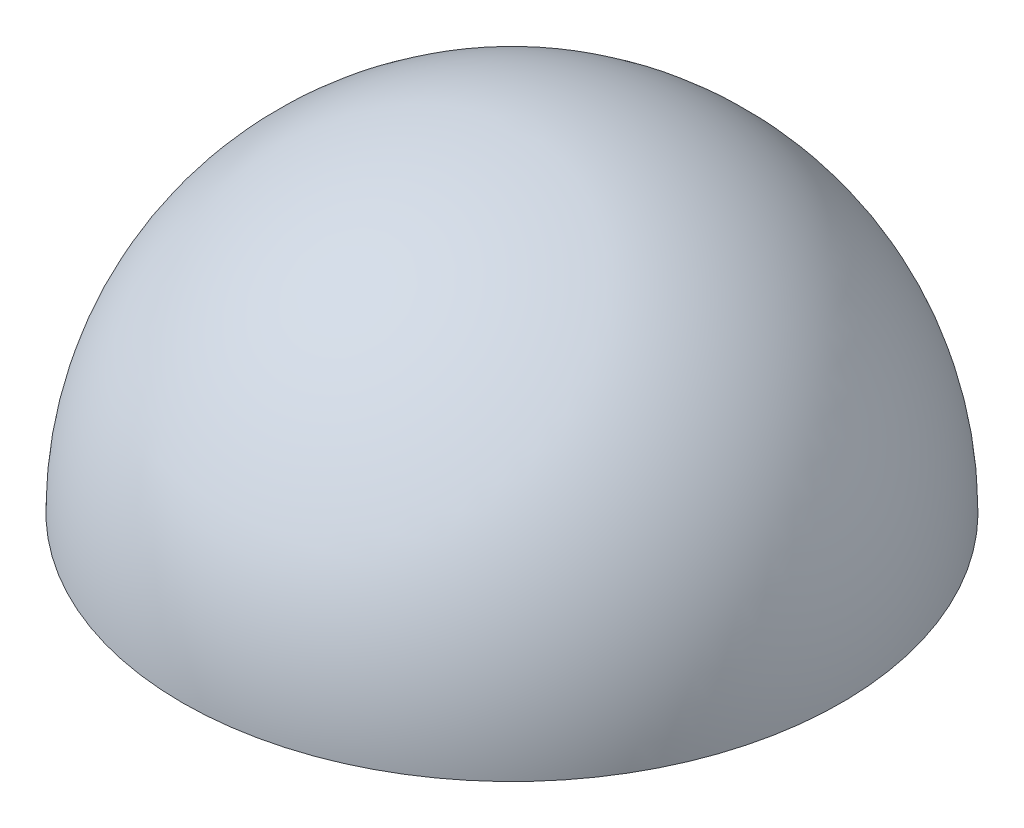
SolidWorks part; units mm, degrees
ref_plane "Front Plane" through (0, 0, 0) normal (0, 0, 1) x (1, 0, 0)
ref_plane "Top Plane" through (0, 0, 0) normal (0, 1, 0) x (1, 0, 0)
ref_plane "Right Plane" through (0, 0, 0) normal (1, 0, 0) x (0, 0, -1)
ref_plane "Plane1" through (0, 76.75, 0) normal (0, -1, 0) x (-1, 0, 0)
sketch "Sketch1" plane through (0, 76.75, 0) normal (0, -1, 0) x (-1, 0, 0)
  line L0 (38.5, 10) -> (-38.5, 10) construction
  line L1 (-13.5, -0.25) -> (7, -0.25)
  arc A0 (-13.5, -0.25) -> (7, -0.25) centre (-3.25, -0.25) ccw
  arc A1 (-13.75, 0) -> (7.25, 0) centre (-3.25, 0) ccw construction
  arc A2 (-13.75, 0) -> (7.25, 0) centre (-3.25, 0) ccw construction
  arc A3 (-13.5, -0.25) -> (7, -0.25) centre (-3.25, -0.25) cw construction
  point P7 (-3.25, -10.5)
  dimension "D1" = 20.5
revolve "Revolve1" add sketch "Sketch1" angle 180 about L1
sketch "Sketch2" plane through (0, 76.75, 0) normal (0, -1, 0) x (1, 0, 0)
  line L1 (1.75, -1.25) -> (4.75, -1.25)
  line L2 (1.75, -1.25) -> (1.75, 1.75)
  line L3 (1.75, 1.75) -> (4.75, 1.75)
  line L4 (4.75, -1.25) -> (4.75, 1.75)
  line L5 (1.75, -1.25) -> (4.75, 1.75) construction
  line L6 (1.75, 1.75) -> (4.75, -1.25) construction
  circle A2 centre (3.25, 0.25) radius 10.25 construction
  circle A3 centre (3.25, 0.25) radius 10.25 construction
  circle A4 centre (3.25, 0.25) radius 1.5 construction
  dimension "D1" = 3
extrude "Cut-Extrude1" cut sketch "Sketch2" against normal blind 6
